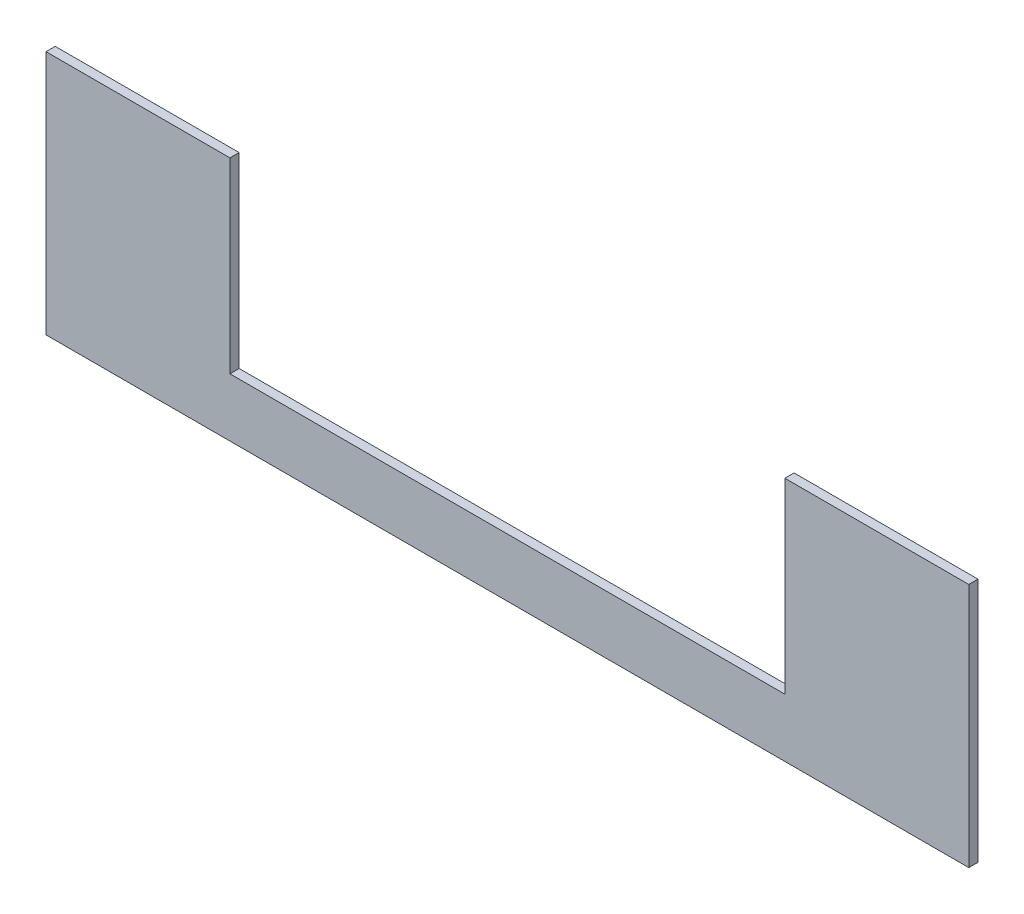
SolidWorks part; units mm, degrees
ref_plane "Plan de face" through (0, 0, 0) normal (0, 0, 1) x (1, 0, 0)
ref_plane "Plan de dessus" through (0, 0, 0) normal (0, 1, 0) x (1, 0, 0)
ref_plane "Plan de droite" through (0, 0, 0) normal (1, 0, 0) x (0, 0, -1)
sketch "Esquisse1" plane through (0, 0, 0) normal (0, 0, 1) x (1, 0, 0)
  line L1 (0, 0) -> (-301, 0)
  line L2 (0, 0) -> (0, 80)
  line L3 (0, 80) -> (-301, 80)
  line L4 (-301, 0) -> (-301, 80)
  dimension "D1" = 80
  dimension "D2" = 301
extrude "Boss.-Extru.1" add sketch "Esquisse1" along normal blind 3
sketch "Esquisse2" plane through (0, 0, 3) normal (0, 0, 1) x (1, 0, 0)
  line L0 (0, 80) -> (-301, 80) construction
  line L1 (-241, 80) -> (-60, 80)
  line L2 (-241, 80) -> (-241, 19)
  line L3 (-241, 19) -> (-60, 19)
  line L4 (-60, 80) -> (-60, 19)
  line L6 (-301, 80) -> (-301, 0) construction
  dimension "D1" = 181
  dimension "D2" = 61
  dimension "D3" = 0
  dimension "D4" = 60
extrude "Enlèv. mat.-Extru.1" cut sketch "Esquisse2" against normal through all
